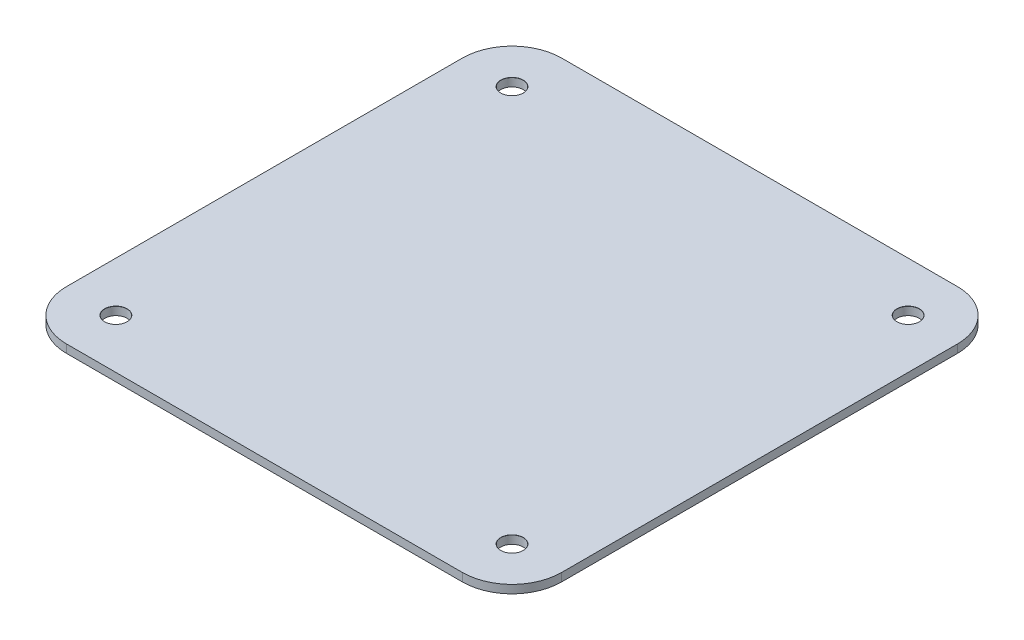
SolidWorks part; units mm, degrees
ref_plane "Front Plane" through (0, 0, 0) normal (0, 0, 1) x (1, 0, 0)
ref_plane "Top Plane" through (0, 0, 0) normal (0, 1, 0) x (1, 0, 0)
ref_plane "Right Plane" through (0, 0, 0) normal (1, 0, 0) x (0, 0, -1)
sketch "Sketch1" plane through (0, 0, 0) normal (0, 1, 0) x (1, 0, 0)
  line L1 (-50, 50) -> (50, 50)
  line L2 (-50, 50) -> (-50, -50)
  line L3 (-50, -50) -> (50, -50)
  line L4 (50, 50) -> (50, -50)
  line L5 (0, -50) -> (0, 50) construction
  line L6 (-50, 0) -> (50, 0) construction
  point P0 (0, 0)
  point P4 (-40, 40)
  point P8 (40, 40)
  point P9 (40, -40)
  point P10 (-40, -40)
  point P11 (0, 0)
  dimension "D1" = 100
  dimension "D3" = 80
  dimension "D2" = 4
extrude "Boss-Extrude1" add sketch "Sketch1" along normal blind 1.66
fillet "Fillet1" radius 10 4 edges at (50, 0.83, 50) (-50, 0.83, -50) (50, 0.83, -50) (-50, 0.83, 50)
sketch "Sketch4" plane through (0, 1.66, 0) normal (0, 1, 0) x (1, 0, 0)
  point P0 (-40, 40)
  point P3 (-40, -40)
  point P6 (40, -40)
  point P9 (40, 40)
hole_wizard "M4 Clearance Hole1" positions "Sketch4" profile "Sketch3" hole size "M4" standard "ISO"
sketch "Sketch3" plane through (-40, 1.66, -40) normal (1, 0, 0) x (0, 0, 1)
  line L0 (0, 0) -> (0, 24)
  line L1 (0, 24) -> (2.25, 22.6481)
  line L2 (2.25, 22.6481) -> (2.25, 0.025)
  line L3 (2.25, 0.025) -> (2.275, 0)
  line L5 (2.275, 0) -> (0, 0)
  line L6 (-2.25, 0.025) -> (-2.275, 0) construction
  line L10 (0, 24) -> (-2.25, 22.6481) construction
  line L11 (0, -6.35) -> (0, 107.95) construction
  dimension "Hole Dia." = 4.5
  dimension "Hole Depth" = 24
  dimension "Near C'Sink Dia." = 4.55
  dimension "Near C'Sink Angle" = 90
  dimension "Drill Angle" = 118
